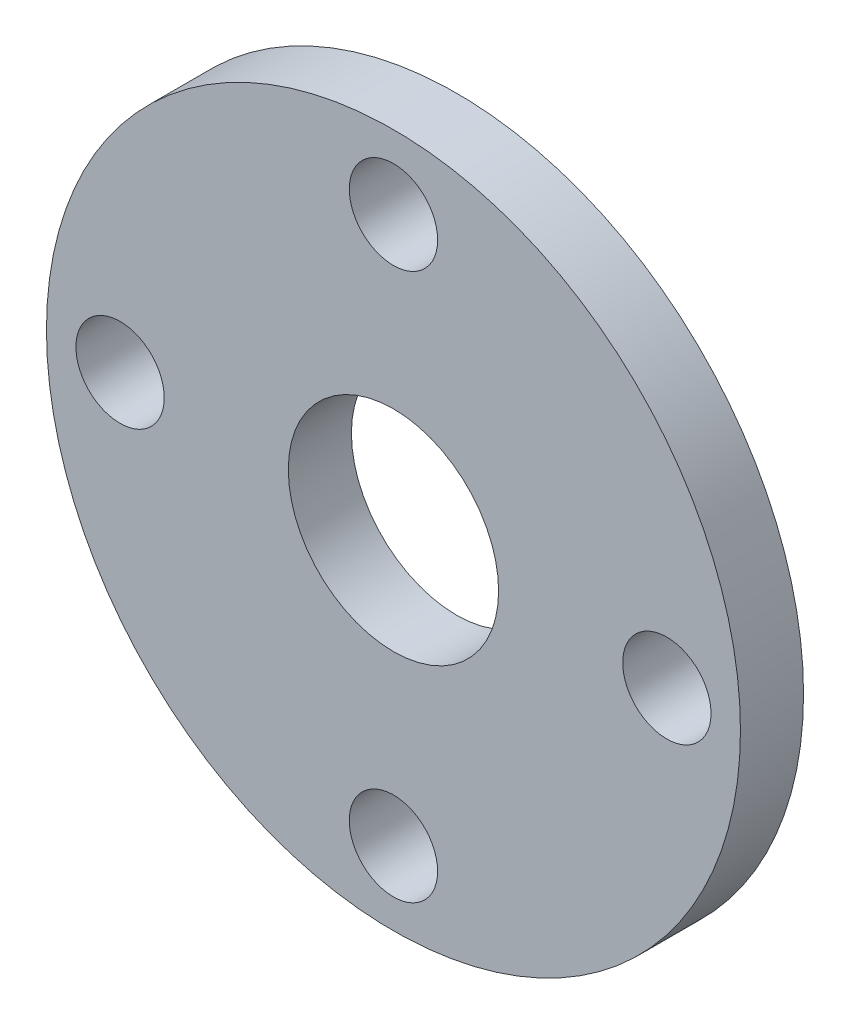
SolidWorks part; units mm, degrees
ref_plane "前视基准面" through (0, 0, 0) normal (0, 0, 1) x (1, 0, 0)
ref_plane "上视基准面" through (0, 0, 0) normal (0, 1, 0) x (1, 0, 0)
ref_plane "右视基准面" through (0, 0, 0) normal (1, 0, 0) x (0, 0, -1)
sketch "草图1" plane through (0, 0, 0) normal (0, 0, 1) x (1, 0, 0)
  circle A0 centre (0, 0) radius 13 construction
  circle A1 centre (0, 13) radius 2.1
  circle A2 centre (13, 0) radius 2.1
  circle A3 centre (0, -13) radius 2.1
  circle A4 centre (-13, 0) radius 2.1
  circle A5 centre (0, 0) radius 5
  circle A6 centre (0, 0) radius 16.5
  dimension "D1" = 26
  dimension "D2" = 4.2
  dimension "D4" = 10
  dimension "D5" = 33
  dimension "D3" = 4
extrude "凸台-拉伸1" add sketch "草图1" along normal blind 3
